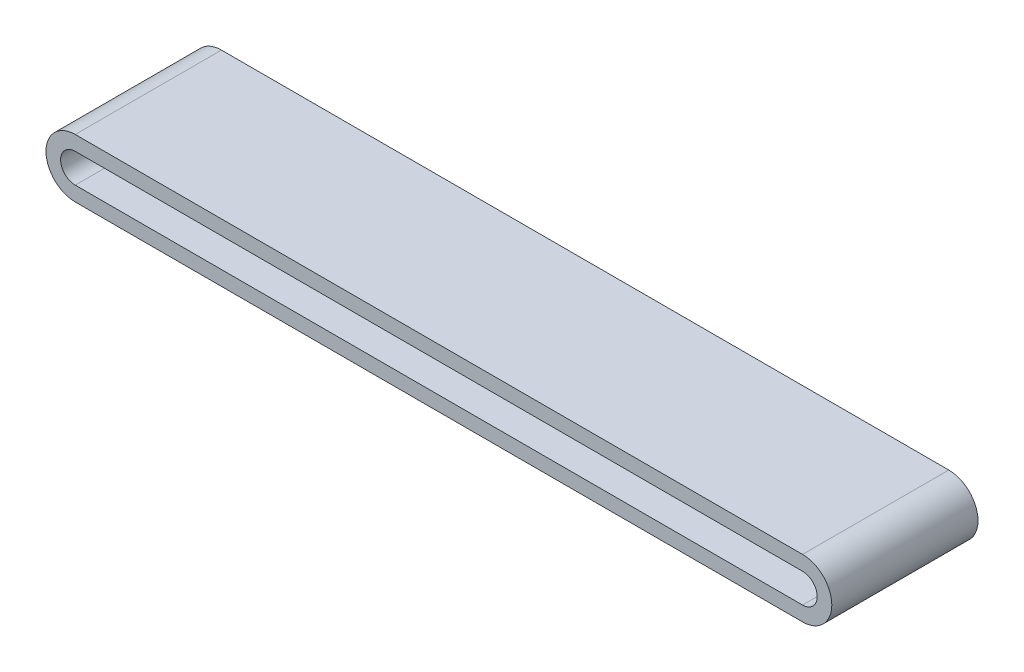
SolidWorks part; units mm, degrees
ref_plane "Piano frontale" through (0, 0, 0) normal (0, 0, 1) x (1, 0, 0)
ref_plane "Piano superiore" through (0, 0, 0) normal (0, 1, 0) x (1, 0, 0)
ref_plane "Piano destro" through (0, 0, 0) normal (1, 0, 0) x (0, 0, -1)
sketch "Schizzo1" plane through (0, 0, 0) normal (0, 0, 1) x (1, 0, 0)
  line L0 (-49.75, 0) -> (49.75, 0) construction
  line L1 (-49.75, 4) -> (49.75, 4)
  line L2 (-49.75, -4) -> (49.75, -4)
  line L3 (-49.75, 0) -> (49.75, 0) construction
  line L4 (-49.75, 2) -> (49.75, 2)
  line L5 (-49.75, -2) -> (49.75, -2)
  line L6 (-53.75, 0) -> (53.75, 0) construction
  arc A0 (-49.75, 4) -> (-49.75, -4) centre (-49.75, 0) ccw
  arc A1 (49.75, -4) -> (49.75, 4) centre (49.75, 0) ccw
  arc A2 (-49.75, 2) -> (-49.75, -2) centre (-49.75, 0) ccw
  arc A3 (49.75, -2) -> (49.75, 2) centre (49.75, 0) ccw
  point P2 (0, 0)
  point P7 (0, 0)
  dimension "D3" = 8
  dimension "D1" = 2
  dimension "D2" = 107.5
extrude "Estrusione-Estrusione1" add sketch "Schizzo1" along normal blind 20
